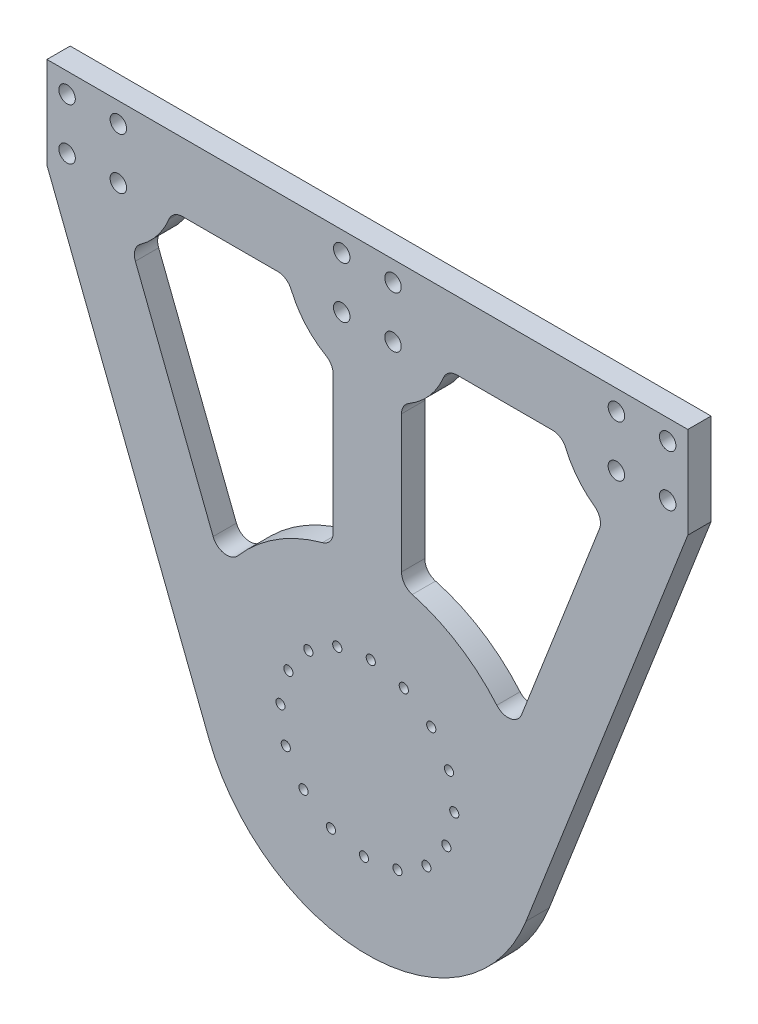
SolidWorks part; units mm, degrees
ref_plane "Front Plane" through (0, 0, 0) normal (0, 0, 1) x (1, 0, 0)
ref_plane "Top Plane" through (0, 0, 0) normal (0, 1, 0) x (1, 0, 0)
ref_plane "Right Plane" through (0, 0, 0) normal (1, 0, 0) x (0, 0, -1)
sketch "Sketch1" plane through (0, 0, 0) normal (0, 0, 1) x (1, 0, 0)
  line L1 (87.5, 121.5) -> (-87.5, 121.5)
  line L3 (0, 0) -> (0, 121.5) construction
  line L4 (-87.5, 121.5) -> (-87.5, 96.5)
  line L5 (-87.5, 96.5) -> (-43.3279, -16.8802)
  line L6 (87.5, 121.5) -> (87.5, 96.5)
  line L7 (87.5, 96.5) -> (43.3279, -16.8802)
  line L8 (43.3279, -16.8802) -> (-43.3279, -16.8802) construction
  circle A0 centre (0, 0) radius 46.5 construction
  arc A1 (-43.3279, -16.8802) -> (43.3279, -16.8802) centre (0, 0) ccw
  dimension "D1" = 93
  dimension "D2" = 175
  dimension "D3" = 121.5
  dimension "D4" = 25
extrude "Boss-Extrude1" add sketch "Sketch1" along normal mid plane 6.35
sketch "Sketch3" plane through (0, 0, -3.175) normal (0, 0, -1) x (-1, 0, 0)
  circle A0 centre (17.4402, -16.1215) radius 1.25 construction
  circle A1 centre (22.282, -8.2203) radius 1.25 construction
  circle A2 centre (9.9432, -21.5684) radius 1.25 construction
  circle A3 centre (0.9324, -23.7317) radius 1.25 construction
  circle A4 centre (-8.2203, -22.282) radius 1.25 construction
  circle A5 centre (-16.1215, -17.4402) radius 1.25 construction
  circle A6 centre (-21.5684, -9.9432) radius 1.25 construction
  circle A7 centre (-23.7317, -0.9324) radius 1.25 construction
  circle A8 centre (-22.282, 8.2203) radius 1.25 construction
  circle A9 centre (-17.4402, 16.1215) radius 1.25 construction
  circle A10 centre (-9.9432, 21.5684) radius 1.25 construction
  circle A11 centre (-0.9324, 23.7317) radius 1.25 construction
  circle A12 centre (8.2203, 22.282) radius 1.25 construction
  circle A13 centre (16.1215, 17.4402) radius 1.25 construction
  circle A14 centre (21.5684, 9.9432) radius 1.25 construction
  circle A15 centre (23.7317, 0.9324) radius 1.25 construction
  circle A16 centre (17.4402, -16.1215) radius 1.25
  circle A17 centre (22.282, -8.2203) radius 1.25
  circle A18 centre (9.9432, -21.5684) radius 1.25
  circle A19 centre (0.9324, -23.7317) radius 1.25
  circle A20 centre (-8.2203, -22.282) radius 1.25
  circle A21 centre (-16.1215, -17.4402) radius 1.25
  circle A22 centre (-21.5684, -9.9432) radius 1.25
  circle A23 centre (-23.7317, -0.9324) radius 1.25
  circle A24 centre (-22.282, 8.2203) radius 1.25
  circle A25 centre (-17.4402, 16.1215) radius 1.25
  circle A26 centre (-9.9432, 21.5684) radius 1.25
  circle A27 centre (-0.9324, 23.7317) radius 1.25
  circle A28 centre (8.2203, 22.282) radius 1.25
  circle A29 centre (16.1215, 17.4402) radius 1.25
  circle A30 centre (21.5684, 9.9432) radius 1.25
  circle A31 centre (23.7317, 0.9324) radius 1.25
extrude "Cut-Extrude2" cut sketch "Sketch3" against normal through all both and the other way through all
ref_plane "Plane1" through (0, 96.5, 0) normal (0, 1, 0) x (1, 0, 0)
ref_plane "Plane2" through (0, 109, 0) normal (0, 1, 0) x (1, 0, 0)
sketch "Sketch6" plane through (0, 0, -3.175) normal (0, 0, -1) x (-1, 0, 0)
  line L0 (0, 0) -> (0, 121.5) construction
  line L1 (-87.5, 121.5) -> (-72.5, 121.5) construction
  line L2 (-87.5, 121.5) -> (-87.5, 91.5) construction
  line L3 (-87.5, 91.5) -> (-72.5, 91.5) construction
  line L4 (-72.5, 121.5) -> (-72.5, 91.5) construction
  line L5 (-87.5, 121.5) -> (87.5, 121.5) construction
  line L6 (-80, 121.5) -> (-80, 106.5) construction
  line L11 (-72.5, 106.5) -> (-87.5, 106.5) construction
  line L12 (-7.5, 121.5) -> (7.5, 121.5) construction
  line L13 (-7.5, 121.5) -> (-7.5, 91.5) construction
  line L14 (-7.5, 91.5) -> (7.5, 91.5) construction
  line L15 (7.5, 121.5) -> (7.5, 91.5) construction
  line L16 (-80, 91.5) -> (-80, 106.5) construction
  circle A0 centre (-80, 114) radius 2.25
  circle A1 centre (-80, 99) radius 2.25
  circle A2 centre (0, 114) radius 2.25
  circle A3 centre (0, 99) radius 2.25
  circle A6 centre (80, 114) radius 2.25
  circle A7 centre (80, 99) radius 2.25
  point P12 (-67.5, 106.5)
  point P18 (0, 121.5)
  point P30 (0, 0)
  point P31 (0, 0)
  point P32 (0, 0)
  point P35 (-80, 114)
  point P38 (-80, 99)
  dimension "D3" = 4.5
  dimension "D1" = 30
  dimension "D2" = 15
sketch "Sketch12" plane through (0, 0, -3.175) normal (0, 0, -1) x (-1, 0, 0)
  line L0 (0, -46.5) -> (0, 121.5) construction
  line L1 (-87.5, 121.5) -> (87.5, 121.5) construction
  line L2 (-82, 116) -> (-87.5, 116) construction
  line L3 (-82, 116) -> (-68, 116) construction
  line L4 (-82, 116) -> (-82, 102) construction
  line L5 (-82, 102) -> (-68, 102) construction
  line L6 (-68, 116) -> (-68, 102) construction
  line L7 (-87.5, 96.5) -> (-87.5, 121.5) construction
  line L8 (-82, 116) -> (-82, 121.5) construction
  line L9 (12.5, 121.5) -> (-12.5, 121.5) construction
  line L11 (-7, 102) -> (7, 102) construction
  line L12 (-7, 102) -> (-7, 116) construction
  line L13 (-7, 116) -> (7, 116) construction
  line L14 (7, 102) -> (7, 116) construction
  circle A0 centre (-7, 102) radius 2.25
  circle A2 centre (7, 102) radius 2.25
  circle A4 centre (7, 116) radius 2.25
  circle A5 centre (-82, 116) radius 2.25
  circle A6 centre (-68, 116) radius 2.25
  circle A7 centre (-68, 102) radius 2.25
  circle A8 centre (-82, 102) radius 2.25
  arc A9 (-43.3279, -16.8802) -> (43.3279, -16.8802) centre (0, 0) ccw construction
  circle A10 centre (82, 102) radius 2.25
  circle A11 centre (68, 102) radius 2.25
  circle A12 centre (68, 116) radius 2.25
  circle A13 centre (82, 116) radius 2.25
  circle A14 centre (-7, 116) radius 2.25
  point P22 (-82, 109)
  point P23 (-7, 109)
  point P24 (0, 116)
  dimension "D3" = 4.5
  dimension "D1" = 5.5
  dimension "D2" = 14
extrude "Cut-Extrude6" cut sketch "Sketch12" against normal through all both and the other way through all
sketch "Sketch13" plane through (0, 0, -3.175) normal (0, 0, -1) x (-1, 0, 0)
  line L0 (-39.4734, 24.5785) -> (-64.5918, 89.0521)
  line L1 (39.4734, 24.5785) -> (64.5553, 88.9585)
  line L2 (-9.3209, 88.5215) -> (-9.3209, 45.5562)
  line L3 (9.3209, 88.5215) -> (9.3209, 45.5562)
  line L6 (68, 101.8874) -> (82, 115.8873) construction
  line L7 (-7, 102) -> (7, 116) construction
  line L8 (-82, 102) -> (-68, 116) construction
  line L9 (53.3228, 102.8582) -> (21.6455, 102.8582)
  line L10 (-53.3545, 102.8582) -> (-21.6455, 102.8582)
  line L11 (25.9578, -10.113) -> (68.8582, 100.0031)
  line L12 (68.8582, 100.0031) -> (68.8582, 102.8582)
  line L13 (68.8582, 102.8582) -> (-68.8582, 102.8582)
  line L14 (-68.8582, 102.8582) -> (-68.8582, 100.0031)
  line L15 (-68.8582, 100.0031) -> (-25.9578, -10.113)
  line L16 (25.9578, -10.113) -> (68.8582, 100.0031) construction
  line L17 (68.8582, 100.0031) -> (68.8582, 102.8582) construction
  line L18 (68.8582, 102.8582) -> (-68.8582, 102.8582) construction
  line L19 (-68.8582, 102.8582) -> (-68.8582, 100.0031) construction
  line L20 (-68.8582, 100.0031) -> (-25.9578, -10.113) construction
  line L23 (0, 0) -> (0, 109) construction
  arc A0 (-39.4734, 24.5785) -> (39.4734, 24.5785) centre (0, 0) cw construction
  circle A1 centre (0, 0) radius 27.8582 construction
  arc A2 (-25.9578, -10.113) -> (25.9578, -10.113) centre (0, 0) ccw
  arc A3 (-25.9578, -10.113) -> (25.9578, -10.113) centre (0, 0) ccw construction
  circle A4 centre (7, 116) radius 2.25 construction
  circle A5 centre (-7, 102) radius 2.25 construction
  circle A6 centre (-68, 116) radius 2.25 construction
  circle A7 centre (-82, 102) radius 2.25 construction
  circle A8 centre (7, 116) radius 2.25 construction
  circle A9 centre (-7, 102) radius 2.25 construction
  circle A10 centre (-68, 116) radius 2.25 construction
  circle A11 centre (-82, 102) radius 2.25 construction
  circle A12 centre (-75, 109) radius 22.5 construction
  circle A13 centre (0, 109) radius 22.5 construction
  circle A14 centre (75, 108.8873) radius 22.5 construction
  arc A15 (-64.5918, 89.0521) -> (-53.3545, 102.8582) centre (-75, 109) ccw
  arc A17 (53.3228, 102.8582) -> (64.5553, 88.9585) centre (75, 108.8873) ccw
  arc A21 (-21.6455, 102.8582) -> (-9.3209, 88.5215) centre (0, 109) ccw
  arc A22 (9.3209, 88.5215) -> (21.6455, 102.8582) centre (0, 109) ccw
  arc A23 (-39.4734, 24.5785) -> (-9.3209, 45.5562) centre (0, 0) cw
  arc A24 (9.3209, 45.5562) -> (39.4734, 24.5785) centre (0, 0) cw
  ellipse E0 centre (82, 115.8873) end of major axis (79.75, 115.8873) minor radius 2.25 construction
  ellipse E1 centre (68, 101.8874) end of major axis (65.75, 101.8874) minor radius 2.25 construction
  ellipse E2 centre (82, 115.8873) end of major axis (79.75, 115.8873) minor radius 2.25 construction
  ellipse E3 centre (68, 101.8874) end of major axis (65.75, 101.8874) minor radius 2.25 construction
  dimension "D2" = 45
  dimension "D3" = 18.6418
  dimension "D4" = 46.5
  dimension "D1" = 18.6418
extrude "Cut-Extrude7" cut sketch "Sketch13" against normal through all both and the other way through all
fillet "Fillet4" radius 4 12 edges at (9.3209, 88.5215, 0) (9.3209, 45.5562, 0) (39.4734, 24.5785, 0) (-64.5553, 88.9585, 0) (-39.4734, 24.5785, 0) (-9.3209, 45.5562, 0) (-9.3209, 88.5215, 0) (-21.6455, 102.8582, 0) (-53.3228, 102.8582, 0) (21.6455, 102.8582, 0) (53.3545, 102.8582, 0) (64.5918, 89.0521, 0)
